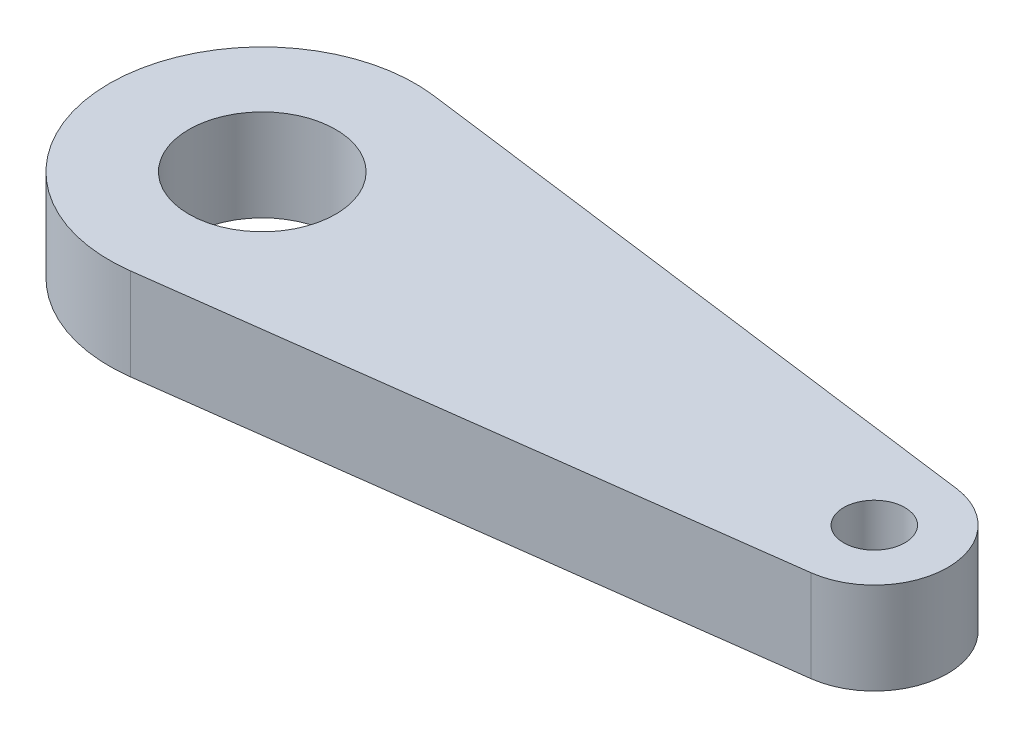
SolidWorks part; units mm, degrees
ref_plane "Front Plane" through (0, 0, 0) normal (0, 0, 1) x (1, 0, 0)
ref_plane "Top Plane" through (0, 0, 0) normal (0, 1, 0) x (1, 0, 0)
ref_plane "Right Plane" through (0, 0, 0) normal (1, 0, 0) x (0, 0, -1)
sketch "Sketch1" plane through (0, 0, 0) normal (0, 1, 0) x (1, 0, 0)
  line L0 (-23.375, -12.3939) -> (25.78, -5.9491)
  line L5 (-23.375, 12.3939) -> (25.78, 5.9491)
  circle A0 centre (-25, 0) radius 6
  arc A1 (-23.375, 12.3939) -> (-23.375, -12.3939) centre (-25, 0) ccw
  arc A2 (25.78, -5.9491) -> (25.78, 5.9491) centre (25, 0) ccw
  circle A3 centre (25, 0) radius 2.5
  point P0 (0, 0)
  dimension "D3" = 5
  dimension "D1" = 12.5
  dimension "D2" = 12
  dimension "D4" = 6
  dimension "D5" = 50
extrude "Boss-Extrude1" add sketch "Sketch1" along normal blind 7.5
